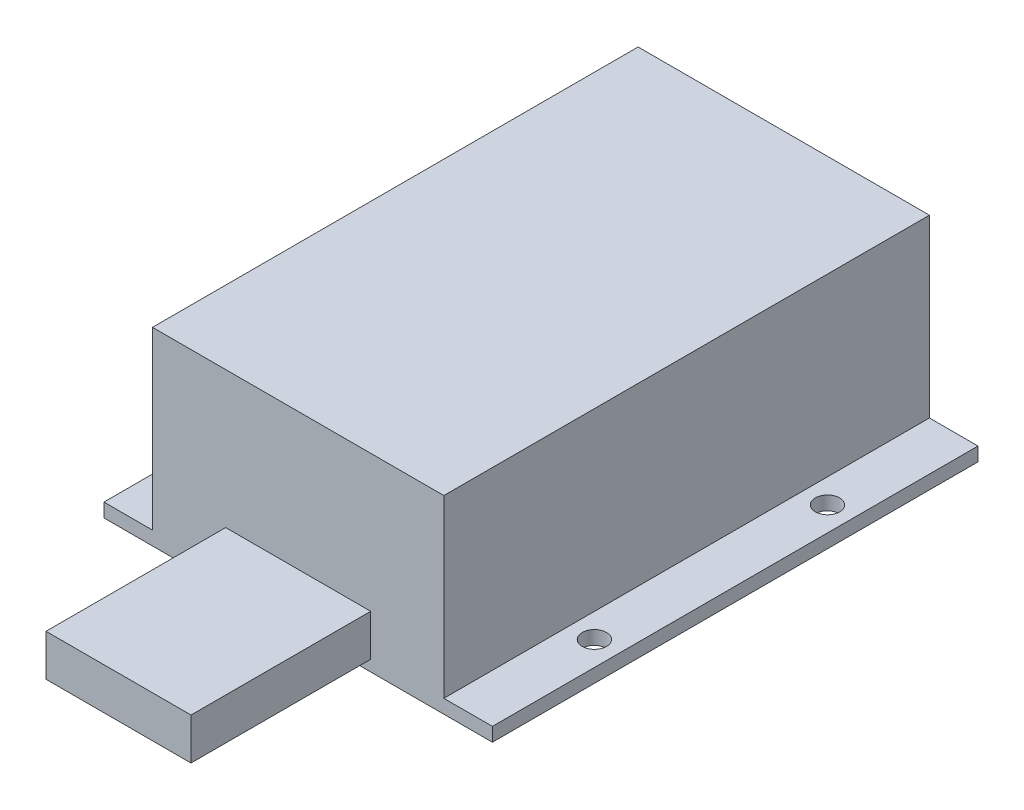
SolidWorks part; units mm, degrees
ref_plane "前视基准面" through (0, 0, 0) normal (0, 0, 1) x (1, 0, 0)
ref_plane "上视基准面" through (0, 0, 0) normal (0, 1, 0) x (1, 0, 0)
ref_plane "右视基准面" through (0, 0, 0) normal (1, 0, 0) x (0, 0, -1)
other "Configuration Table"
sketch "草图2" plane through (0, 0, 0) normal (0, 0, 1) x (1, 0, 0)
  line L0 (0, 0) -> (0, -43.5109) construction
  line L1 (-30, 19.5) -> (30, 19.5)
  line L3 (-40, -19.5) -> (40, -19.5)
  line L5 (-30, 19.5) -> (-30, -16.6667)
  line L6 (-30, -16.6667) -> (-40, -16.6667)
  line L7 (-40, -16.6667) -> (-40, -19.5)
  line L8 (40, -16.6667) -> (40, -19.5)
  line L9 (30, -16.6667) -> (40, -16.6667)
  line L10 (30, 19.5) -> (30, -16.6667)
  point P0 (0, 0)
  dimension "D1" = 60
  dimension "D2" = 39
  dimension "D3" = 80
extrude "凸台-拉伸1" add sketch "草图2" along normal mid plane 100
sketch "草图3" plane through (0, -16.6667, 0) normal (0, 1, 0) x (1, 0, 0)
  line L0 (0, 50) -> (0, 102.0555) construction
  line L2 (-30, 50) -> (-40, 50) construction
  line L3 (-30, -50) -> (-40, -50) construction
  circle A0 centre (-35, 24) radius 2.5
  circle A1 centre (35, 24) radius 2.5
  circle A2 centre (-35, -24) radius 2.5
  circle A3 centre (35, -24) radius 2.5
  dimension "D1" = 5
  dimension "D4" = 5
  dimension "D2" = 26
  dimension "D3" = 70
  dimension "D5" = 48
  dimension "D6" = 26
extrude "切除-拉伸1" cut sketch "草图3" against normal through all
sketch "草图4" plane through (0, 0, 50) normal (0, 0, 1) x (1, 0, 0)
  line L1 (-14.9319, -8.6773) -> (14.9319, -8.6773)
  line L2 (-14.9319, -8.6773) -> (-14.9319, -17.2412)
  line L3 (-14.9319, -17.2412) -> (14.9319, -17.2412)
  line L4 (14.9319, -8.6773) -> (14.9319, -17.2412)
  line L5 (-14.9319, -8.6773) -> (14.9319, -17.2412) construction
  line L6 (-14.9319, -17.2412) -> (14.9319, -8.6773) construction
  point P0 (0, -12.9593)
extrude "凸台-拉伸2" add sketch "草图4" along normal blind 37
